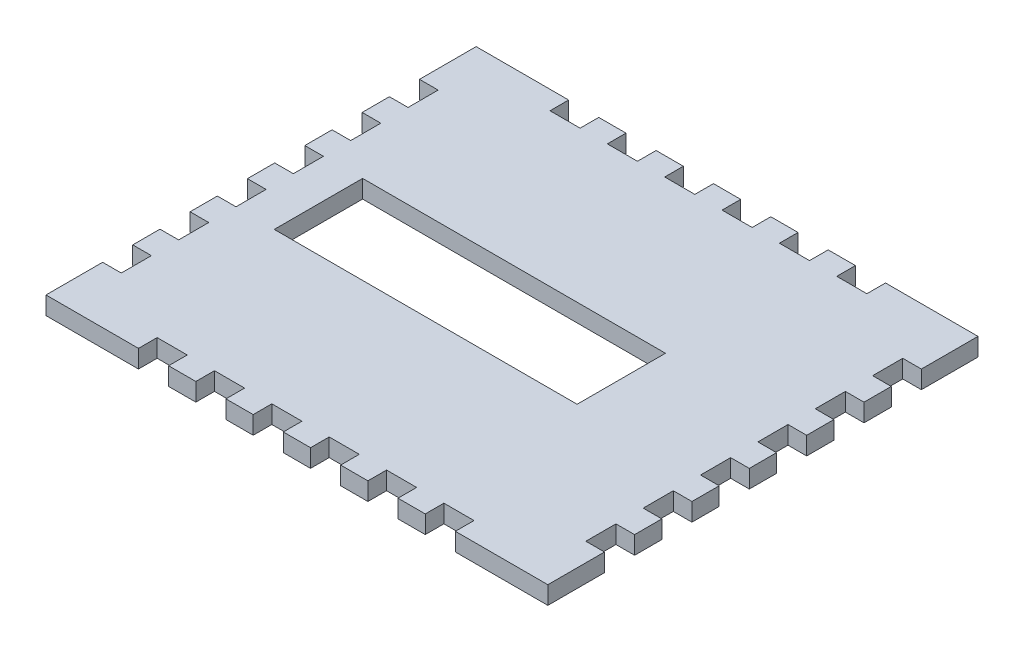
SolidWorks part; units mm, degrees
ref_plane "Front Plane" through (0, 0, 0) normal (0, 0, 1) x (1, 0, 0)
ref_plane "Top Plane" through (0, 0, 0) normal (0, 1, 0) x (1, 0, 0)
ref_plane "Right Plane" through (0, 0, 0) normal (1, 0, 0) x (0, 0, -1)
sketch "Sketch1" plane through (0, 0, 0) normal (0, 1, 0) x (1, 0, 0)
  line L1 (-44.45, -38.1) -> (44.45, -38.1)
  line L2 (-44.45, -38.1) -> (-44.45, 38.1)
  line L3 (-44.45, 38.1) -> (44.45, 38.1)
  line L4 (44.45, -38.1) -> (44.45, 38.1)
  line L5 (-44.45, -38.1) -> (44.45, 38.1) construction
  line L6 (-44.45, 38.1) -> (44.45, -38.1) construction
  line L7 (-37.465, -11) -> (22.535, -11) construction
  line L8 (-37.465, -11) -> (-37.465, 11) construction
  line L9 (-37.465, 11) -> (22.535, 11) construction
  line L10 (22.535, -11) -> (22.535, 11) construction
  line L11 (-34.29, -7.825) -> (-34.29, -11) construction
  line L12 (-34.29, -7.825) -> (19.36, -7.825)
  line L13 (-34.29, -7.825) -> (-34.29, 7.825)
  line L14 (-34.29, 7.825) -> (19.36, 7.825)
  line L15 (19.36, -7.825) -> (19.36, 7.825)
  line L16 (-37.465, -7.825) -> (-34.29, -7.825) construction
  line L17 (19.36, 7.825) -> (19.36, 11) construction
  line L18 (19.36, 7.825) -> (22.535, 7.825) construction
  point P0 (0, 0)
  point P10 (22.535, 0)
  dimension "D3" = 22
  dimension "D1" = 88.9
  dimension "D2" = 76.2
  dimension "D4" = 60
  dimension "D5" = 6.985
  dimension "D6" = 3.175
extrude "Boss-Extrude1" add sketch "Sketch1" along normal blind 3.175
sketch "Sketch2" plane through (0, 0, 0) normal (0, 1, 0) x (1, 0, 0)
  line L1 (-44.45, 38.1) -> (-44.45, -38.1) construction
  line L29 (0, 0) -> (11.4095, 0) construction
  line L35 (-28.067, -38.1) -> (-22.733, -38.1)
  line L51 (-22.733, -34.798) -> (-22.733, -38.1)
  line L52 (-28.067, -34.798) -> (-22.733, -34.798)
  line L53 (-28.067, -38.1) -> (-28.067, -34.798)
  line L58 (-44.45, -12.573) -> (-41.148, -12.573)
  line L83 (-44.45, -22.733) -> (-41.148, -22.733)
  line L84 (-44.45, -22.733) -> (-44.45, -28.067)
  line L85 (-44.45, -28.067) -> (-41.148, -28.067)
  line L86 (-41.148, -22.733) -> (-41.148, -28.067)
  line L91 (0, 0) -> (0, 13.7627) construction
  line L124 (-44.45, -12.573) -> (-44.45, -17.907)
  line L125 (-44.45, -17.907) -> (-41.148, -17.907)
  line L146 (-41.148, -12.573) -> (-41.148, -17.907)
  line L147 (-44.45, -2.413) -> (-41.148, -2.413)
  line L148 (-44.45, -2.413) -> (-44.45, -7.747)
  line L149 (-44.45, -7.747) -> (-41.148, -7.747)
  line L150 (-41.148, -2.413) -> (-41.148, -7.747)
  line L151 (-44.45, 7.747) -> (-41.148, 7.747)
  line L152 (-44.45, 7.747) -> (-44.45, 2.413)
  line L153 (-44.45, 2.413) -> (-41.148, 2.413)
  line L154 (-41.148, 7.747) -> (-41.148, 2.413)
  line L155 (-44.45, 17.907) -> (-41.148, 17.907)
  line L156 (-44.45, 17.907) -> (-44.45, 12.573)
  line L157 (-44.45, 12.573) -> (-41.148, 12.573)
  line L158 (-41.148, 17.907) -> (-41.148, 12.573)
  line L159 (-44.45, 28.067) -> (-41.148, 28.067)
  line L160 (-44.45, 28.067) -> (-44.45, 22.733)
  line L161 (-44.45, 22.733) -> (-41.148, 22.733)
  line L162 (-41.148, 28.067) -> (-41.148, 22.733)
  line L163 (41.148, 28.067) -> (41.148, 22.733)
  line L164 (44.45, 22.733) -> (41.148, 22.733)
  line L165 (44.45, 28.067) -> (44.45, 22.733)
  line L166 (44.45, 28.067) -> (41.148, 28.067)
  line L167 (41.148, 17.907) -> (41.148, 12.573)
  line L168 (44.45, 12.573) -> (41.148, 12.573)
  line L169 (44.45, 17.907) -> (44.45, 12.573)
  line L170 (44.45, 17.907) -> (41.148, 17.907)
  line L171 (41.148, 7.747) -> (41.148, 2.413)
  line L172 (44.45, 2.413) -> (41.148, 2.413)
  line L173 (44.45, 7.747) -> (44.45, 2.413)
  line L174 (44.45, 7.747) -> (41.148, 7.747)
  line L175 (41.148, -2.413) -> (41.148, -7.747)
  line L176 (44.45, -7.747) -> (41.148, -7.747)
  line L177 (44.45, -2.413) -> (44.45, -7.747)
  line L178 (44.45, -2.413) -> (41.148, -2.413)
  line L179 (41.148, -12.573) -> (41.148, -17.907)
  line L180 (44.45, -17.907) -> (41.148, -17.907)
  line L181 (44.45, -12.573) -> (44.45, -17.907)
  line L182 (41.148, -22.733) -> (41.148, -28.067)
  line L183 (44.45, -28.067) -> (41.148, -28.067)
  line L184 (44.45, -22.733) -> (44.45, -28.067)
  line L185 (44.45, -22.733) -> (41.148, -22.733)
  line L186 (44.45, -12.573) -> (41.148, -12.573)
  line L187 (-17.907, -38.1) -> (-12.573, -38.1)
  line L188 (-12.573, -34.798) -> (-12.573, -38.1)
  line L189 (-17.907, -34.798) -> (-12.573, -34.798)
  line L190 (-17.907, -38.1) -> (-17.907, -34.798)
  line L191 (-7.747, -38.1) -> (-2.413, -38.1)
  line L192 (-2.413, -34.798) -> (-2.413, -38.1)
  line L193 (-7.747, -34.798) -> (-2.413, -34.798)
  line L194 (-7.747, -38.1) -> (-7.747, -34.798)
  line L195 (2.413, -38.1) -> (7.747, -38.1)
  line L196 (7.747, -34.798) -> (7.747, -38.1)
  line L197 (2.413, -34.798) -> (7.747, -34.798)
  line L198 (2.413, -38.1) -> (2.413, -34.798)
  line L199 (12.573, -38.1) -> (17.907, -38.1)
  line L200 (17.907, -34.798) -> (17.907, -38.1)
  line L201 (12.573, -34.798) -> (17.907, -34.798)
  line L202 (12.573, -38.1) -> (12.573, -34.798)
  line L203 (22.733, -38.1) -> (28.067, -38.1)
  line L204 (28.067, -34.798) -> (28.067, -38.1)
  line L205 (22.733, -34.798) -> (28.067, -34.798)
  line L206 (22.733, -38.1) -> (22.733, -34.798)
  line L207 (22.733, 38.1) -> (22.733, 34.798)
  line L208 (22.733, 34.798) -> (28.067, 34.798)
  line L209 (28.067, 34.798) -> (28.067, 38.1)
  line L210 (22.733, 38.1) -> (28.067, 38.1)
  line L211 (12.573, 38.1) -> (12.573, 34.798)
  line L212 (12.573, 34.798) -> (17.907, 34.798)
  line L213 (17.907, 34.798) -> (17.907, 38.1)
  line L214 (12.573, 38.1) -> (17.907, 38.1)
  line L215 (2.413, 38.1) -> (2.413, 34.798)
  line L216 (2.413, 34.798) -> (7.747, 34.798)
  line L217 (7.747, 34.798) -> (7.747, 38.1)
  line L218 (2.413, 38.1) -> (7.747, 38.1)
  line L219 (-7.747, 38.1) -> (-7.747, 34.798)
  line L220 (-7.747, 34.798) -> (-2.413, 34.798)
  line L221 (-2.413, 34.798) -> (-2.413, 38.1)
  line L222 (-7.747, 38.1) -> (-2.413, 38.1)
  line L223 (-17.907, 38.1) -> (-17.907, 34.798)
  line L224 (-17.907, 34.798) -> (-12.573, 34.798)
  line L225 (-12.573, 34.798) -> (-12.573, 38.1)
  line L226 (-17.907, 38.1) -> (-12.573, 38.1)
  line L227 (-28.067, 38.1) -> (-28.067, 34.798)
  line L228 (-28.067, 34.798) -> (-22.733, 34.798)
  line L229 (-22.733, 34.798) -> (-22.733, 38.1)
  line L230 (-28.067, 38.1) -> (-22.733, 38.1)
  line L231 (44.45, 38.1) -> (-44.45, 38.1) construction
  point P3 (-44.45, -25.4)
  dimension "D1" = 6
  dimension "D2" = 5.334
  dimension "D4" = 25.4
  dimension "D7" = 5.334
  dimension "D8" = 3.302
  dimension "D5" = 6
extrude "Cut-Extrude1" cut sketch "Sketch2" along normal through all
